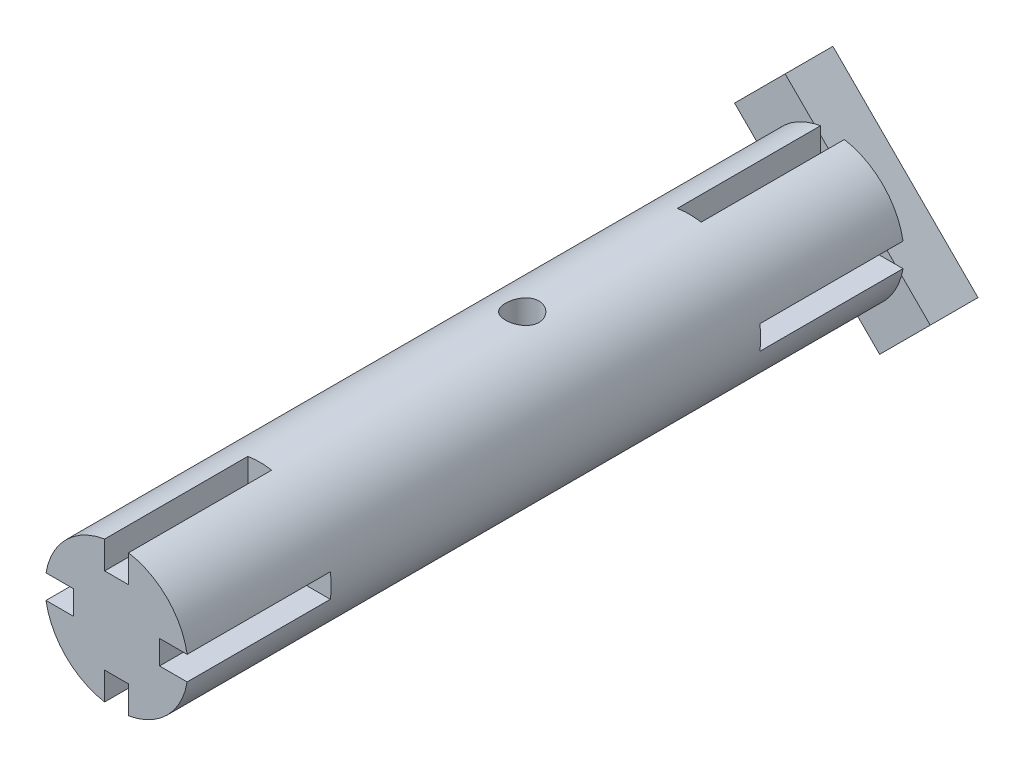
SolidWorks part; units mm, degrees
ref_plane "Front Plane" through (0, 0, 0) normal (0, 0, 1) x (1, 0, 0)
ref_plane "Top Plane" through (0, 0, 0) normal (0, 1, 0) x (1, 0, 0)
ref_plane "Right Plane" through (0, 0, 0) normal (1, 0, 0) x (0, 0, -1)
sketch "Sketch1" plane through (0, 0, 0) normal (0, 0, 1) x (1, 0, 0)
  circle A0 centre (0, 0) radius 1.5
  dimension "D1" = 3
extrude "Boss-Extrude1" add sketch "Sketch1" along normal blind 15
sketch "Sketch2" plane through (0, 0, 0) normal (0, 0, -1) x (-1, 0, 0)
  line L0 (0, 1.5) -> (0, -1.5) construction
  line L1 (-1.5, 0) -> (1.5, 0) construction
  line L2 (1.6473, 0.25) -> (0.9, 0.25)
  line L3 (0.9, 0.25) -> (0.9, -0.25)
  line L4 (0.9, -0.25) -> (1.6473, -0.25)
  line L5 (1.6473, 0.25) -> (1.6473, -0.25)
  circle A0 centre (0, 0) radius 1.5 construction
  dimension "D1" = 0.25
  dimension "D2" = 0.5
  dimension "D3" = 0.6
extrude "Cut-Extrude1" cut sketch "Sketch2" against normal blind 3
pattern_circular "CirPattern1" count 4 over 360 about axis through (0, 0, 0) along (0, 0, 1) of "Cut-Extrude1"
ref_plane "Plane1" through (0, 0, 7.5) normal (0, 0, -1) x (-1, 0, 0)
mirror "Mirror1" about plane through (0, 0, 7.5) normal (0, 0, -1) of "CirPattern1", "Cut-Extrude1"
sketch "Sketch6" plane through (0, 0, 0) normal (0, 0, -1) x (-1, 0, 0)
  line L0 (0, 0) -> (-1.0607, -1.0607) construction
  line L1 (-1.0607, -1.0607) -> (-1.7134, -1.7134) construction
  line L2 (-0.9899, -2.0506) -> (-2.0506, -0.9899)
  line L3 (-2.0506, -0.9899) -> (0.9899, 2.0506)
  line L4 (0.9899, 2.0506) -> (2.0506, 0.9899)
  line L5 (-0.9899, -2.0506) -> (2.0506, 0.9899)
  arc A2 (-1.479, -0.25) -> (-0.25, -1.479) centre (0, 0) ccw construction
  point P12 (-1.5203, -1.5203)
  point P13 (1.5203, 1.5203)
  point P17 (1.4281, 1.2357)
  dimension "D1" = 0.75
  dimension "D2" = 2.15
  dimension "D3" = 2.15
extrude "Boss-Extrude5" add sketch "Sketch6" along normal blind 1
sketch "Sketch7" plane through (0, 0, 0) normal (0, 1, 0) x (1, 0, 0)
  line L0 (0.9745, -6) -> (-3, -6) construction
  line L1 (-1.5, -3) -> (-1.5, -12) construction
  circle A0 centre (0, -6.5) radius 0.35
  dimension "D2" = 0.7
  dimension "D1" = 0.5
  dimension "D3" = 1.5
extrude "Cut-Extrude2" cut sketch "Sketch7" against normal up to surface and the other way up to surface up to face at (0, 0, 1.2) other way up to face at (0, 0, 1.2)
